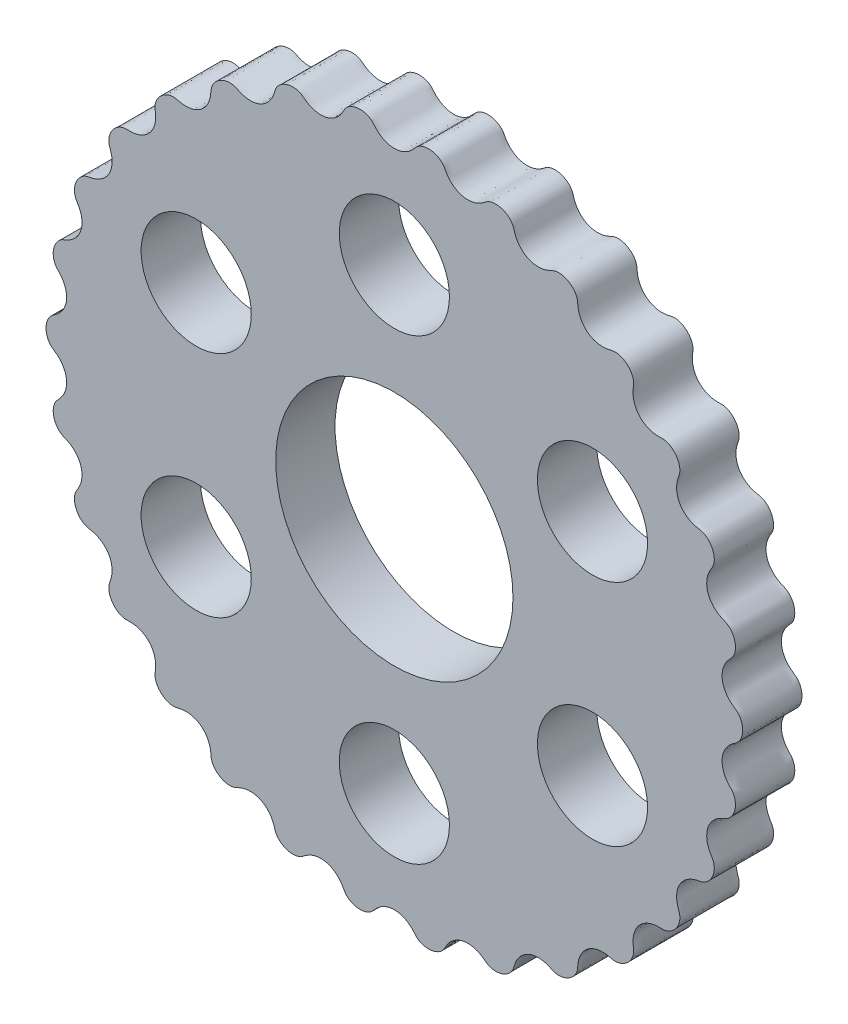
SolidWorks part; units mm, degrees
ref_plane "Front Plane" through (0, 0, 0) normal (0, 0, 1) x (1, 0, 0)
ref_plane "Top Plane" through (0, 0, 0) normal (0, 1, 0) x (1, 0, 0)
ref_plane "Right Plane" through (0, 0, 0) normal (1, 0, 0) x (0, 0, -1)
curve "Curve1"
sketch "Sketch1" plane through (0, 0, 0) normal (0, 0, 1) x (1, 0, 0)
  spline S0 degree 3 poles (1.507, 39.2179) (0, 38.6713) (-1.507, 39.2179) (-2.1962, 39.8832) (-2.4453, 40.1783) (-2.572, 40.3207) (-2.6813, 40.4255) (-2.8099, 40.5269) (-2.9733, 40.6297) (-3.1768, 40.7277) (-3.4191, 40.8108) (-3.6937, 40.869) (-3.9905, 40.8941) (-4.2968, 40.8813) (-4.5991, 40.8301) (-4.8841, 40.7439) (-5.1407, 40.6299) (-5.3604, 40.4982) (-5.5391, 40.36) (-5.6775, 40.2255) (-5.7822, 40.0996) (-5.8674, 39.9743) (-5.9616, 39.8087) (-6.144, 39.4683) (-6.6798, 38.6743) (-8.0402, 37.8262) (-9.6279, 38.0476) (-10.4403, 38.555) (-10.7454, 38.7919) (-10.8989, 38.9048) (-11.0277, 38.9846) (-11.1746, 39.0571) (-11.3557, 39.1237) (-11.5752, 39.1772) (-11.8294, 39.2082) (-12.1101, 39.2079) (-12.4056, 39.1708) (-12.7026, 39.0946) (-12.9876, 38.9817) (-13.2485, 38.8381) (-13.4758, 38.6732) (-13.6633, 38.4987) (-13.8094, 38.3265) (-13.9168, 38.1661) (-13.993, 38.0212) (-14.0503, 37.8809) (-14.108, 37.6993) (-14.2157, 37.3284) (-14.5746, 36.4403) (-15.729, 35.328) (-17.3281, 35.2144) (-18.2282, 35.5419) (-18.5759, 35.7101) (-18.7495, 35.7886) (-18.8921, 35.8399) (-19.0508, 35.8803) (-19.2418, 35.9077) (-19.4676, 35.9145) (-19.7228, 35.8919) (-19.9973, 35.8333) (-20.2786, 35.7355) (-20.5533, 35.5993) (-20.8086, 35.4295) (-21.0339, 35.2348) (-21.2219, 35.0264) (-21.3691, 34.8167) (-21.4761, 34.6178) (-21.5478, 34.4386) (-21.5923, 34.281) (-21.6191, 34.1319) (-21.6379, 33.9422) (-21.666, 33.5571) (-21.8325, 32.6138) (-22.7304, 31.2857) (-24.2709, 30.8422) (-25.2195, 30.9753) (-25.5945, 31.0676) (-25.7807, 31.1083) (-25.9308, 31.1289) (-26.0944, 31.1353) (-26.287, 31.1225) (-26.5092, 31.0821) (-26.7541, 31.007) (-27.0105, 30.8926) (-27.2653, 30.7385) (-27.5056, 30.5481) (-27.7201, 30.329) (-27.9, 30.0917) (-28.0406, 29.8487) (-28.1409, 29.613) (-28.2042, 29.3962) (-28.2371, 29.206) (-28.2478, 29.0426) (-28.2431, 28.8912) (-28.222, 28.7017) (-28.1695, 28.3191) (-28.1362, 27.3619) (-28.7384, 25.8761) (-30.153, 25.122) (-31.1085, 25.055) (-31.4945, 25.0673) (-31.6851, 25.0684) (-31.8362, 25.0573) (-31.9976, 25.0296) (-32.1833, 24.977) (-32.3923, 24.8913) (-32.6162, 24.7669) (-32.8432, 24.6017) (-33.0604, 24.398) (-33.2559, 24.1618) (-33.4201, 23.9029) (-33.5467, 23.6333) (-33.6337, 23.3664) (-33.6828, 23.115) (-33.6997, 22.8898) (-33.6924, 22.6969) (-33.6688, 22.5349) (-33.6327, 22.3877) (-33.5727, 22.2069) (-33.4418, 21.8435) (-33.2102, 20.9141) (-33.4903, 19.3356) (-34.7172, 18.3039) (-35.6379, 18.0397) (-36.0181, 17.9714) (-36.2047, 17.9329) (-36.3502, 17.8906) (-36.5023, 17.83) (-36.673, 17.7399) (-36.8596, 17.6127) (-37.0528, 17.4444) (-37.2405, 17.2357) (-37.4105, 16.9912) (-37.5527, 16.7195) (-37.6594, 16.4321) (-37.7273, 16.1421) (-37.7569, 15.863) (-37.7527, 15.6069) (-37.7224, 15.383) (-37.6751, 15.1959) (-37.6184, 15.0423) (-37.5524, 14.9059) (-37.4561, 14.7414) (-37.2525, 14.4133) (-36.8328, 13.5523) (-36.7786, 11.9501) (-37.7642, 10.6858) (-38.6098, 10.2359) (-38.9674, 10.0901) (-39.142, 10.0137) (-39.2755, 9.9421) (-39.4117, 9.8511) (-39.56, 9.7275) (-39.716, 9.5642) (-39.87, 9.3595) (-40.0101, 9.1163) (-40.1257, 8.8418) (-40.2082, 8.5465) (-40.2529, 8.2432) (-40.259, 7.9455) (-40.2299, 7.6663) (-40.1725, 7.4166) (-40.0963, 7.204) (-40.0112, 7.0308) (-39.9238, 6.8923) (-39.8309, 6.7726) (-39.7025, 6.6317) (-39.4351, 6.3531) (-38.8456, 5.5981) (-38.4595, 4.0423) (-39.1606, 2.6006) (-39.8943, 1.9848) (-40.2138, 1.7678) (-40.3686, 1.6568) (-40.4843, 1.559) (-40.5986, 1.4417) (-40.7179, 1.2899) (-40.8367, 1.0978) (-40.9447, 0.8655) (-41.0312, 0.5985) (-41.0872, 0.306) (-41.1065, 0) (-41.0872, -0.306) (-41.0312, -0.5985) (-40.9447, -0.8655) (-40.8367, -1.0978) (-40.7179, -1.2899) (-40.5986, -1.4417) (-40.4843, -1.559) (-40.3686, -1.6568) (-40.2138, -1.7678) (-39.8943, -1.9848) (-39.1606, -2.6006) (-38.4595, -4.0423) (-38.8456, -5.5981) (-39.4351, -6.3531) (-39.7025, -6.6317) (-39.8309, -6.7726) (-39.9238, -6.8923) (-40.0112, -7.0308) (-40.0963, -7.204) (-40.1725, -7.4166) (-40.2299, -7.6663) (-40.259, -7.9455) (-40.2529, -8.2432) (-40.2082, -8.5465) (-40.1257, -8.8418) (-40.0101, -9.1163) (-39.87, -9.3595) (-39.716, -9.5642) (-39.56, -9.7275) (-39.4117, -9.8511) (-39.2755, -9.9421) (-39.142, -10.0137) (-38.9674, -10.0901) (-38.6098, -10.2359) (-37.7642, -10.6858) (-36.7786, -11.9501) (-36.8328, -13.5523) (-37.2525, -14.4133) (-37.4561, -14.7414) (-37.5524, -14.9059) (-37.6184, -15.0423) (-37.6751, -15.1959) (-37.7224, -15.383) (-37.7527, -15.6069) (-37.7569, -15.863) (-37.7273, -16.1421) (-37.6594, -16.4321) (-37.5527, -16.7195) (-37.4105, -16.9912) (-37.2405, -17.2357) (-37.0528, -17.4444) (-36.8596, -17.6127) (-36.673, -17.7399) (-36.5023, -17.83) (-36.3502, -17.8906) (-36.2047, -17.9329) (-36.0181, -17.9714) (-35.6379, -18.0397) (-34.7172, -18.3039) (-33.4903, -19.3356) (-33.2102, -20.9141) (-33.4418, -21.8435) (-33.5727, -22.2069) (-33.6327, -22.3877) (-33.6688, -22.5349) (-33.6924, -22.6969) (-33.6997, -22.8898) (-33.6828, -23.115) (-33.6337, -23.3664) (-33.5467, -23.6333) (-33.4201, -23.9029) (-33.2559, -24.1618) (-33.0604, -24.398) (-32.8432, -24.6017) (-32.6162, -24.7669) (-32.3923, -24.8913) (-32.1833, -24.977) (-31.9976, -25.0296) (-31.8362, -25.0573) (-31.6851, -25.0684) (-31.4945, -25.0673) (-31.1085, -25.055) (-30.153, -25.122) (-28.7384, -25.8761) (-28.1362, -27.3619) (-28.1695, -28.3191) (-28.222, -28.7017) (-28.2431, -28.8912) (-28.2478, -29.0426) (-28.2371, -29.206) (-28.2042, -29.3962) (-28.1409, -29.613) (-28.0406, -29.8487) (-27.9, -30.0917) (-27.7201, -30.329) (-27.5056, -30.5481) (-27.2653, -30.7385) (-27.0105, -30.8926) (-26.7541, -31.007) (-26.5092, -31.0821) (-26.287, -31.1225) (-26.0944, -31.1353) (-25.9308, -31.1289) (-25.7807, -31.1083) (-25.5945, -31.0676) (-25.2195, -30.9753) (-24.2709, -30.8422) (-22.7304, -31.2857) (-21.8325, -32.6138) (-21.666, -33.5571) (-21.6379, -33.9422) (-21.6191, -34.1319) (-21.5923, -34.281) (-21.5478, -34.4386) (-21.4761, -34.6178) (-21.3691, -34.8167) (-21.2219, -35.0264) (-21.0339, -35.2348) (-20.8086, -35.4295) (-20.5533, -35.5993) (-20.2786, -35.7355) (-19.9973, -35.8333) (-19.7228, -35.8919) (-19.4676, -35.9145) (-19.2418, -35.9077) (-19.0508, -35.8803) (-18.8921, -35.8399) (-18.7495, -35.7886) (-18.5759, -35.7101) (-18.2282, -35.5419) (-17.3281, -35.2144) (-15.729, -35.328) (-14.5746, -36.4403) (-14.2157, -37.3284) (-14.108, -37.6993) (-14.0503, -37.8809) (-13.993, -38.0212) (-13.9168, -38.1661) (-13.8094, -38.3265) (-13.6633, -38.4987) (-13.4758, -38.6732) (-13.2485, -38.8381) (-12.9876, -38.9817) (-12.7026, -39.0946) (-12.4056, -39.1708) (-12.1101, -39.2079) (-11.8294, -39.2082) (-11.5752, -39.1772) (-11.3557, -39.1237) (-11.1746, -39.0571) (-11.0277, -38.9846) (-10.8989, -38.9048) (-10.7454, -38.7919) (-10.4403, -38.555) (-9.6279, -38.0476) (-8.0402, -37.8262) (-6.6798, -38.6743) (-6.144, -39.4683) (-5.9616, -39.8087) (-5.8674, -39.9743) (-5.7822, -40.0996) (-5.6775, -40.2255) (-5.5391, -40.36) (-5.3604, -40.4982) (-5.1407, -40.6299) (-4.8841, -40.7439) (-4.5991, -40.8301) (-4.2968, -40.8813) (-3.9905, -40.8941) (-3.6937, -40.869) (-3.4191, -40.8108) (-3.1768, -40.7277) (-2.9733, -40.6297) (-2.8099, -40.5269) (-2.6813, -40.4255) (-2.572, -40.3207) (-2.4453, -40.1783) (-2.1962, -39.8832) (-1.507, -39.2179) (0, -38.6713) (1.507, -39.2179) (2.1962, -39.8832) (2.4453, -40.1783) (2.572, -40.3207) (2.6813, -40.4255) (2.8099, -40.5269) (2.9733, -40.6297) (3.1768, -40.7277) (3.4191, -40.8108) (3.6937, -40.869) (3.9905, -40.8941) (4.2968, -40.8813) (4.5991, -40.8301) (4.8841, -40.7439) (5.1407, -40.6299) (5.3604, -40.4982) (5.5391, -40.36) (5.6775, -40.2255) (5.7822, -40.0996) (5.8674, -39.9743) (5.9616, -39.8087) (6.144, -39.4683) (6.6798, -38.6743) (8.0402, -37.8262) (9.6279, -38.0476) (10.4403, -38.555) (10.7454, -38.7919) (10.8989, -38.9048) (11.0277, -38.9846) (11.1746, -39.0571) (11.3557, -39.1237) (11.5752, -39.1772) (11.8294, -39.2082) (12.1101, -39.2079) (12.4056, -39.1708) (12.7026, -39.0946) (12.9876, -38.9817) (13.2485, -38.8381) (13.4758, -38.6732) (13.6633, -38.4987) (13.8094, -38.3265) (13.9168, -38.1661) (13.993, -38.0212) (14.0503, -37.8809) (14.108, -37.6993) (14.2157, -37.3284) (14.5746, -36.4403) (15.729, -35.328) (17.3281, -35.2144) (18.2282, -35.5419) (18.5759, -35.7101) (18.7495, -35.7886) (18.8921, -35.8399) (19.0508, -35.8803) (19.2418, -35.9077) (19.4676, -35.9145) (19.7228, -35.8919) (19.9973, -35.8333) (20.2786, -35.7355) (20.5533, -35.5993) (20.8086, -35.4295) (21.0339, -35.2348) (21.2219, -35.0264) (21.3691, -34.8167) (21.4761, -34.6178) (21.5478, -34.4386) (21.5923, -34.281) (21.6191, -34.1319) (21.6379, -33.9422) (21.666, -33.5571) (21.8325, -32.6138) (22.7304, -31.2857) (24.2709, -30.8422) (25.2195, -30.9753) (25.5945, -31.0676) (25.7807, -31.1083) (25.9308, -31.1289) (26.0944, -31.1353) (26.287, -31.1225) (26.5092, -31.0821) (26.7541, -31.007) (27.0105, -30.8926) (27.2653, -30.7385) (27.5056, -30.5481) (27.7201, -30.329) (27.9, -30.0917) (28.0406, -29.8487) (28.1409, -29.613) (28.2042, -29.3962) (28.2371, -29.206) (28.2478, -29.0426) (28.2431, -28.8912) (28.222, -28.7017) (28.1695, -28.3191) (28.1362, -27.3619) (28.7384, -25.8761) (30.153, -25.122) (31.1085, -25.055) (31.4945, -25.0673) (31.6851, -25.0684) (31.8362, -25.0573) (31.9976, -25.0296) (32.1833, -24.977) (32.3923, -24.8913) (32.6162, -24.7669) (32.8432, -24.6017) (33.0604, -24.398) (33.2559, -24.1618) (33.4201, -23.9029) (33.5467, -23.6333) (33.6337, -23.3664) (33.6828, -23.115) (33.6997, -22.8898) (33.6924, -22.6969) (33.6688, -22.5349) (33.6327, -22.3877) (33.5727, -22.2069) (33.4418, -21.8435) (33.2102, -20.9141) (33.4903, -19.3356) (34.7172, -18.3039) (35.6379, -18.0397) (36.0181, -17.9714) (36.2047, -17.9329) (36.3502, -17.8906) (36.5023, -17.83) (36.673, -17.7399) (36.8596, -17.6127) (37.0528, -17.4444) (37.2405, -17.2357) (37.4105, -16.9912) (37.5527, -16.7195) (37.6594, -16.4321) (37.7273, -16.1421) (37.7569, -15.863) (37.7527, -15.6069) (37.7224, -15.383) (37.6751, -15.1959) (37.6184, -15.0423) (37.5524, -14.9059) (37.4561, -14.7414) (37.2525, -14.4133) (36.8328, -13.5523) (36.7786, -11.9501) (37.7642, -10.6858) (38.6098, -10.2359) (38.9674, -10.0901) (39.142, -10.0137) (39.2755, -9.9421) (39.4117, -9.8511) (39.56, -9.7275) (39.716, -9.5642) (39.87, -9.3595) (40.0101, -9.1163) (40.1257, -8.8418) (40.2082, -8.5465) (40.2529, -8.2432) (40.259, -7.9455) (40.2299, -7.6663) (40.1725, -7.4166) (40.0963, -7.204) (40.0112, -7.0308) (39.9238, -6.8923) (39.8309, -6.7726) (39.7025, -6.6317) (39.4351, -6.3531) (38.8456, -5.5981) (38.4595, -4.0423) (39.1606, -2.6006) (39.8943, -1.9848) (40.2138, -1.7678) (40.3686, -1.6568) (40.4843, -1.559) (40.5986, -1.4417) (40.7179, -1.2899) (40.8367, -1.0978) (40.9447, -0.8655) (41.0312, -0.5985) (41.0872, -0.306) (41.1065, 0) (41.0872, 0.306) (41.0312, 0.5985) (40.9447, 0.8655) (40.8367, 1.0978) (40.7179, 1.2899) (40.5986, 1.4417) (40.4843, 1.559) (40.3686, 1.6568) (40.2138, 1.7678) (39.8943, 1.9848) (39.1606, 2.6006) (38.4595, 4.0423) (38.8456, 5.5981) (39.4351, 6.3531) (39.7025, 6.6317) (39.8309, 6.7726) (39.9238, 6.8923) (40.0112, 7.0308) (40.0963, 7.204) (40.1725, 7.4166) (40.2299, 7.6663) (40.259, 7.9455) (40.2529, 8.2432) (40.2082, 8.5465) (40.1257, 8.8418) (40.0101, 9.1163) (39.87, 9.3595) (39.716, 9.5642) (39.56, 9.7275) (39.4117, 9.8511) (39.2755, 9.9421) (39.142, 10.0137) (38.9674, 10.0901) (38.6098, 10.2359) (37.7642, 10.6858) (36.7786, 11.9501) (36.8328, 13.5523) (37.2525, 14.4133) (37.4561, 14.7414) (37.5524, 14.9059) (37.6184, 15.0423) (37.6751, 15.1959) (37.7224, 15.383) (37.7527, 15.6069) (37.7569, 15.863) (37.7273, 16.1421) (37.6594, 16.4321) (37.5527, 16.7195) (37.4105, 16.9912) (37.2405, 17.2357) (37.0528, 17.4444) (36.8596, 17.6127) (36.673, 17.7399) (36.5023, 17.83) (36.3502, 17.8906) (36.2047, 17.9329) (36.0181, 17.9714) (35.6379, 18.0397) (34.7172, 18.3039) (33.4903, 19.3356) (33.2102, 20.9141) (33.4418, 21.8435) (33.5727, 22.2069) (33.6327, 22.3877) (33.6688, 22.5349) (33.6924, 22.6969) (33.6997, 22.8898) (33.6828, 23.115) (33.6337, 23.3664) (33.5467, 23.6333) (33.4201, 23.9029) (33.2559, 24.1618) (33.0604, 24.398) (32.8432, 24.6017) (32.6162, 24.7669) (32.3923, 24.8913) (32.1833, 24.977) (31.9976, 25.0296) (31.8362, 25.0573) (31.6851, 25.0684) (31.4945, 25.0673) (31.1085, 25.055) (30.153, 25.122) (28.7384, 25.8761) (28.1362, 27.3619) (28.1695, 28.3191) (28.222, 28.7017) (28.2431, 28.8912) (28.2478, 29.0426) (28.2371, 29.206) (28.2042, 29.3962) (28.1409, 29.613) (28.0406, 29.8487) (27.9, 30.0917) (27.7201, 30.329) (27.5056, 30.5481) (27.2653, 30.7385) (27.0105, 30.8926) (26.7541, 31.007) (26.5092, 31.0821) (26.287, 31.1225) (26.0944, 31.1353) (25.9308, 31.1289) (25.7807, 31.1083) (25.5945, 31.0676) (25.2195, 30.9753) (24.2709, 30.8422) (22.7304, 31.2857) (21.8325, 32.6138) (21.666, 33.5571) (21.6379, 33.9422) (21.6191, 34.1319) (21.5923, 34.281) (21.5478, 34.4386) (21.4761, 34.6178) (21.3691, 34.8167) (21.2219, 35.0264) (21.0339, 35.2348) (20.8086, 35.4295) (20.5533, 35.5993) (20.2786, 35.7355) (19.9973, 35.8333) (19.7228, 35.8919) (19.4676, 35.9145) (19.2418, 35.9077) (19.0508, 35.8803) (18.8921, 35.8399) (18.7495, 35.7886) (18.5759, 35.7101) (18.2282, 35.5419) (17.3281, 35.2144) (15.729, 35.328) (14.5746, 36.4403) (14.2157, 37.3284) (14.108, 37.6993) (14.0503, 37.8809) (13.993, 38.0212) (13.9168, 38.1661) (13.8094, 38.3265) (13.6633, 38.4987) (13.4758, 38.6732) (13.2485, 38.8381) (12.9876, 38.9817) (12.7026, 39.0946) (12.4056, 39.1708) (12.1101, 39.2079) (11.8294, 39.2082) (11.5752, 39.1772) (11.3557, 39.1237) (11.1746, 39.0571) (11.0277, 38.9846) (10.8989, 38.9048) (10.7454, 38.7919) (10.4403, 38.555) (9.6279, 38.0476) (8.0402, 37.8262) (6.6798, 38.6743) (6.144, 39.4683) (5.9616, 39.8087) (5.8674, 39.9743) (5.7822, 40.0996) (5.6775, 40.2255) (5.5391, 40.36) (5.3604, 40.4982) (5.1407, 40.6299) (4.8841, 40.7439) (4.5991, 40.8301) (4.2968, 40.8813) (3.9905, 40.8941) (3.6937, 40.869) (3.4191, 40.8108) (3.1768, 40.7277) (2.9733, 40.6297) (2.8099, 40.5269) (2.6813, 40.4255) (2.572, 40.3207) (2.4453, 40.1783) (2.1962, 39.8832) (1.507, 39.2179) (0, 38.6713) (-1.507, 39.2179) knots -0.009771 -0.008826 -0.006349 0 0.006349 0.008826 0.009771 0.010301 0.010776 0.01132 0.011975 0.012747 0.013626 0.01459 0.015613 0.016667 0.01772 0.018743 0.019707 0.020586 0.021359 0.022014 0.022558 0.023032 0.023562 0.024507 0.026985 0.033333 0.039682 0.042159 0.043104 0.043635 0.044109 0.044653 0.045308 0.046081 0.04696 0.047924 0.048947 0.05 0.051053 0.052076 0.05304 0.053919 0.054692 0.055347 0.055891 0.056365 0.056896 0.057841 0.060318 0.066667 0.073015 0.075493 0.076438 0.076968 0.077442 0.077986 0.078641 0.079414 0.080293 0.081257 0.08228 0.083333 0.084387 0.08541 0.086374 0.087253 0.088025 0.08868 0.089224 0.089699 0.090229 0.091174 0.093651 0.1 0.106349 0.108826 0.109771 0.110301 0.110776 0.11132 0.111975 0.112747 0.113626 0.11459 0.115613 0.116667 0.11772 0.118743 0.119707 0.120586 0.121359 0.122014 0.122558 0.123032 0.123562 0.124507 0.126985 0.133333 0.139682 0.142159 0.143104 0.143635 0.144109 0.144653 0.145308 0.146081 0.14696 0.147924 0.148947 0.15 0.151053 0.152076 0.15304 0.153919 0.154692 0.155347 0.155891 0.156365 0.156896 0.157841 0.160318 0.166667 0.173015 0.175493 0.176437 0.176968 0.177442 0.177986 0.178641 0.179414 0.180293 0.181257 0.18228 0.183333 0.184387 0.18541 0.186374 0.187253 0.188025 0.18868 0.189224 0.189699 0.190229 0.191174 0.193651 0.2 0.206349 0.208826 0.209771 0.210301 0.210776 0.21132 0.211975 0.212747 0.213626 0.21459 0.215613 0.216667 0.21772 0.218743 0.219707 0.220586 0.221359 0.222014 0.222558 0.223032 0.223563 0.224507 0.226985 0.233333 0.239682 0.242159 0.243104 0.243635 0.244109 0.244653 0.245308 0.246081 0.24696 0.247924 0.248947 0.25 0.251053 0.252076 0.25304 0.253919 0.254692 0.255347 0.255891 0.256365 0.256896 0.257841 0.260318 0.266667 0.273015 0.275493 0.276437 0.276968 0.277442 0.277986 0.278641 0.279414 0.280293 0.281257 0.28228 0.283333 0.284387 0.28541 0.286374 0.287253 0.288025 0.28868 0.289224 0.289699 0.290229 0.291174 0.293651 0.3 0.306349 0.308826 0.309771 0.310301 0.310776 0.31132 0.311975 0.312747 0.313626 0.31459 0.315613 0.316667 0.31772 0.318743 0.319707 0.320586 0.321359 0.322014 0.322558 0.323032 0.323563 0.324507 0.326985 0.333333 0.339682 0.342159 0.343104 0.343635 0.344109 0.344653 0.345308 0.346081 0.34696 0.347924 0.348947 0.35 0.351053 0.352076 0.35304 0.353919 0.354692 0.355347 0.355891 0.356365 0.356896 0.357841 0.360318 0.366667 0.373015 0.375493 0.376438 0.376968 0.377442 0.377986 0.378641 0.379414 0.380293 0.381257 0.38228 0.383333 0.384387 0.38541 0.386374 0.387253 0.388025 0.38868 0.389224 0.389699 0.390229 0.391174 0.393651 0.4 0.406349 0.408826 0.409771 0.410301 0.410776 0.41132 0.411975 0.412747 0.413626 0.41459 0.415613 0.416667 0.41772 0.418743 0.419707 0.420586 0.421359 0.422014 0.422558 0.423032 0.423562 0.424507 0.426985 0.433333 0.439682 0.442159 0.443104 0.443635 0.444109 0.444653 0.445308 0.446081 0.44696 0.447924 0.448947 0.45 0.451053 0.452076 0.45304 0.453919 0.454692 0.455347 0.455891 0.456365 0.456896 0.457841 0.460318 0.466667 0.473015 0.475493 0.476438 0.476968 0.477442 0.477986 0.478641 0.479414 0.480293 0.481257 0.48228 0.483333 0.484387 0.48541 0.486374 0.487253 0.488025 0.48868 0.489224 0.489699 0.490229 0.491174 0.493651 0.5 0.506349 0.508826 0.509771 0.510301 0.510776 0.51132 0.511975 0.512747 0.513626 0.51459 0.515613 0.516667 0.51772 0.518743 0.519707 0.520586 0.521359 0.522014 0.522558 0.523032 0.523562 0.524507 0.526985 0.533333 0.539682 0.542159 0.543104 0.543635 0.544109 0.544653 0.545308 0.546081 0.54696 0.547924 0.548947 0.55 0.551053 0.552076 0.55304 0.553919 0.554692 0.555347 0.555891 0.556365 0.556896 0.557841 0.560318 0.566667 0.573015 0.575493 0.576438 0.576968 0.577442 0.577986 0.578641 0.579414 0.580293 0.581257 0.58228 0.583333 0.584387 0.58541 0.586374 0.587253 0.588025 0.58868 0.589224 0.589699 0.590229 0.591174 0.593651 0.6 0.606349 0.608826 0.609771 0.610301 0.610776 0.61132 0.611975 0.612747 0.613626 0.61459 0.615613 0.616667 0.61772 0.618743 0.619707 0.620586 0.621359 0.622014 0.622558 0.623032 0.623562 0.624507 0.626985 0.633333 0.639682 0.642159 0.643104 0.643635 0.644109 0.644653 0.645308 0.646081 0.64696 0.647924 0.648947 0.65 0.651053 0.652076 0.65304 0.653919 0.654692 0.655347 0.655891 0.656365 0.656896 0.657841 0.660318 0.666667 0.673015 0.675493 0.676437 0.676968 0.677442 0.677986 0.678641 0.679414 0.680293 0.681257 0.68228 0.683333 0.684387 0.68541 0.686374 0.687253 0.688025 0.68868 0.689224 0.689699 0.690229 0.691174 0.693651 0.7 0.706349 0.708826 0.709771 0.710301 0.710776 0.71132 0.711975 0.712747 0.713626 0.71459 0.715613 0.716667 0.71772 0.718743 0.719707 0.720586 0.721359 0.722014 0.722558 0.723032 0.723563 0.724507 0.726985 0.733333 0.739682 0.742159 0.743104 0.743635 0.744109 0.744653 0.745308 0.746081 0.74696 0.747924 0.748947 0.75 0.751053 0.752076 0.75304 0.753919 0.754692 0.755347 0.755891 0.756365 0.756896 0.757841 0.760318 0.766667 0.773015 0.775493 0.776437 0.776968 0.777442 0.777986 0.778641 0.779414 0.780293 0.781257 0.78228 0.783333 0.784387 0.78541 0.786374 0.787253 0.788025 0.78868 0.789224 0.789699 0.790229 0.791174 0.793651 0.8 0.806349 0.808826 0.809771 0.810301 0.810776 0.81132 0.811975 0.812747 0.813626 0.81459 0.815613 0.816667 0.81772 0.818743 0.819707 0.820586 0.821359 0.822014 0.822558 0.823032 0.823563 0.824507 0.826985 0.833333 0.839682 0.842159 0.843104 0.843635 0.844109 0.844653 0.845308 0.846081 0.84696 0.847924 0.848947 0.85 0.851053 0.852076 0.85304 0.853919 0.854692 0.855347 0.855891 0.856365 0.856896 0.857841 0.860318 0.866667 0.873015 0.875493 0.876438 0.876968 0.877442 0.877986 0.878641 0.879414 0.880293 0.881257 0.88228 0.883333 0.884387 0.88541 0.886374 0.887253 0.888025 0.88868 0.889224 0.889699 0.890229 0.891174 0.893651 0.9 0.906349 0.908826 0.909771 0.910301 0.910776 0.91132 0.911975 0.912747 0.913626 0.91459 0.915613 0.916667 0.91772 0.918743 0.919707 0.920586 0.921359 0.922014 0.922558 0.923032 0.923562 0.924507 0.926985 0.933333 0.939682 0.942159 0.943104 0.943635 0.944109 0.944653 0.945308 0.946081 0.94696 0.947924 0.948947 0.95 0.951053 0.952076 0.95304 0.953919 0.954692 0.955347 0.955891 0.956365 0.956896 0.957841 0.960318 0.966667 0.973015 0.975493 0.976438 0.976968 0.977442 0.977986 0.978641 0.979414 0.980293 0.981257 0.98228 0.983333 0.984387 0.98541 0.986374 0.987253 0.988025 0.98868 0.989224 0.989699 0.990229 0.991174 0.993651 1 1.006349 1.008826 1.009771 only from (0, 38.9) to (0, 38.9) construction
  spline S1 degree 3 poles (1.507, 39.2179) (0, 38.6713) (-1.507, 39.2179) (-2.1962, 39.8832) (-2.4453, 40.1783) (-2.572, 40.3207) (-2.6813, 40.4255) (-2.8099, 40.5269) (-2.9733, 40.6297) (-3.1768, 40.7277) (-3.4191, 40.8108) (-3.6937, 40.869) (-3.9905, 40.8941) (-4.2968, 40.8813) (-4.5991, 40.8301) (-4.8841, 40.7439) (-5.1407, 40.6299) (-5.3604, 40.4982) (-5.5391, 40.36) (-5.6775, 40.2255) (-5.7822, 40.0996) (-5.8674, 39.9743) (-5.9616, 39.8087) (-6.144, 39.4683) (-6.6798, 38.6743) (-8.0402, 37.8262) (-9.6279, 38.0476) (-10.4403, 38.555) (-10.7454, 38.7919) (-10.8989, 38.9048) (-11.0277, 38.9846) (-11.1746, 39.0571) (-11.3557, 39.1237) (-11.5752, 39.1772) (-11.8294, 39.2082) (-12.1101, 39.2079) (-12.4056, 39.1708) (-12.7026, 39.0946) (-12.9876, 38.9817) (-13.2485, 38.8381) (-13.4758, 38.6732) (-13.6633, 38.4987) (-13.8094, 38.3265) (-13.9168, 38.1661) (-13.993, 38.0212) (-14.0503, 37.8809) (-14.108, 37.6993) (-14.2157, 37.3284) (-14.5746, 36.4403) (-15.729, 35.328) (-17.3281, 35.2144) (-18.2282, 35.5419) (-18.5759, 35.7101) (-18.7495, 35.7886) (-18.8921, 35.8399) (-19.0508, 35.8803) (-19.2418, 35.9077) (-19.4676, 35.9145) (-19.7228, 35.8919) (-19.9973, 35.8333) (-20.2786, 35.7355) (-20.5533, 35.5993) (-20.8086, 35.4295) (-21.0339, 35.2348) (-21.2219, 35.0264) (-21.3691, 34.8167) (-21.4761, 34.6178) (-21.5478, 34.4386) (-21.5923, 34.281) (-21.6191, 34.1319) (-21.6379, 33.9422) (-21.666, 33.5571) (-21.8325, 32.6138) (-22.7304, 31.2857) (-24.2709, 30.8422) (-25.2195, 30.9753) (-25.5945, 31.0676) (-25.7807, 31.1083) (-25.9308, 31.1289) (-26.0944, 31.1353) (-26.287, 31.1225) (-26.5092, 31.0821) (-26.7541, 31.007) (-27.0105, 30.8926) (-27.2653, 30.7385) (-27.5056, 30.5481) (-27.7201, 30.329) (-27.9, 30.0917) (-28.0406, 29.8487) (-28.1409, 29.613) (-28.2042, 29.3962) (-28.2371, 29.206) (-28.2478, 29.0426) (-28.2431, 28.8912) (-28.222, 28.7017) (-28.1695, 28.3191) (-28.1362, 27.3619) (-28.7384, 25.8761) (-30.153, 25.122) (-31.1085, 25.055) (-31.4945, 25.0673) (-31.6851, 25.0684) (-31.8362, 25.0573) (-31.9976, 25.0296) (-32.1833, 24.977) (-32.3923, 24.8913) (-32.6162, 24.7669) (-32.8432, 24.6017) (-33.0604, 24.398) (-33.2559, 24.1618) (-33.4201, 23.9029) (-33.5467, 23.6333) (-33.6337, 23.3664) (-33.6828, 23.115) (-33.6997, 22.8898) (-33.6924, 22.6969) (-33.6688, 22.5349) (-33.6327, 22.3877) (-33.5727, 22.2069) (-33.4418, 21.8435) (-33.2102, 20.9141) (-33.4903, 19.3356) (-34.7172, 18.3039) (-35.6379, 18.0397) (-36.0181, 17.9714) (-36.2047, 17.9329) (-36.3502, 17.8906) (-36.5023, 17.83) (-36.673, 17.7399) (-36.8596, 17.6127) (-37.0528, 17.4444) (-37.2405, 17.2357) (-37.4105, 16.9912) (-37.5527, 16.7195) (-37.6594, 16.4321) (-37.7273, 16.1421) (-37.7569, 15.863) (-37.7527, 15.6069) (-37.7224, 15.383) (-37.6751, 15.1959) (-37.6184, 15.0423) (-37.5524, 14.9059) (-37.4561, 14.7414) (-37.2525, 14.4133) (-36.8328, 13.5523) (-36.7786, 11.9501) (-37.7642, 10.6858) (-38.6098, 10.2359) (-38.9674, 10.0901) (-39.142, 10.0137) (-39.2755, 9.9421) (-39.4117, 9.8511) (-39.56, 9.7275) (-39.716, 9.5642) (-39.87, 9.3595) (-40.0101, 9.1163) (-40.1257, 8.8418) (-40.2082, 8.5465) (-40.2529, 8.2432) (-40.259, 7.9455) (-40.2299, 7.6663) (-40.1725, 7.4166) (-40.0963, 7.204) (-40.0112, 7.0308) (-39.9238, 6.8923) (-39.8309, 6.7726) (-39.7025, 6.6317) (-39.4351, 6.3531) (-38.8456, 5.5981) (-38.4595, 4.0423) (-39.1606, 2.6006) (-39.8943, 1.9848) (-40.2138, 1.7678) (-40.3686, 1.6568) (-40.4843, 1.559) (-40.5986, 1.4417) (-40.7179, 1.2899) (-40.8367, 1.0978) (-40.9447, 0.8655) (-41.0312, 0.5985) (-41.0872, 0.306) (-41.1065, 0) (-41.0872, -0.306) (-41.0312, -0.5985) (-40.9447, -0.8655) (-40.8367, -1.0978) (-40.7179, -1.2899) (-40.5986, -1.4417) (-40.4843, -1.559) (-40.3686, -1.6568) (-40.2138, -1.7678) (-39.8943, -1.9848) (-39.1606, -2.6006) (-38.4595, -4.0423) (-38.8456, -5.5981) (-39.4351, -6.3531) (-39.7025, -6.6317) (-39.8309, -6.7726) (-39.9238, -6.8923) (-40.0112, -7.0308) (-40.0963, -7.204) (-40.1725, -7.4166) (-40.2299, -7.6663) (-40.259, -7.9455) (-40.2529, -8.2432) (-40.2082, -8.5465) (-40.1257, -8.8418) (-40.0101, -9.1163) (-39.87, -9.3595) (-39.716, -9.5642) (-39.56, -9.7275) (-39.4117, -9.8511) (-39.2755, -9.9421) (-39.142, -10.0137) (-38.9674, -10.0901) (-38.6098, -10.2359) (-37.7642, -10.6858) (-36.7786, -11.9501) (-36.8328, -13.5523) (-37.2525, -14.4133) (-37.4561, -14.7414) (-37.5524, -14.9059) (-37.6184, -15.0423) (-37.6751, -15.1959) (-37.7224, -15.383) (-37.7527, -15.6069) (-37.7569, -15.863) (-37.7273, -16.1421) (-37.6594, -16.4321) (-37.5527, -16.7195) (-37.4105, -16.9912) (-37.2405, -17.2357) (-37.0528, -17.4444) (-36.8596, -17.6127) (-36.673, -17.7399) (-36.5023, -17.83) (-36.3502, -17.8906) (-36.2047, -17.9329) (-36.0181, -17.9714) (-35.6379, -18.0397) (-34.7172, -18.3039) (-33.4903, -19.3356) (-33.2102, -20.9141) (-33.4418, -21.8435) (-33.5727, -22.2069) (-33.6327, -22.3877) (-33.6688, -22.5349) (-33.6924, -22.6969) (-33.6997, -22.8898) (-33.6828, -23.115) (-33.6337, -23.3664) (-33.5467, -23.6333) (-33.4201, -23.9029) (-33.2559, -24.1618) (-33.0604, -24.398) (-32.8432, -24.6017) (-32.6162, -24.7669) (-32.3923, -24.8913) (-32.1833, -24.977) (-31.9976, -25.0296) (-31.8362, -25.0573) (-31.6851, -25.0684) (-31.4945, -25.0673) (-31.1085, -25.055) (-30.153, -25.122) (-28.7384, -25.8761) (-28.1362, -27.3619) (-28.1695, -28.3191) (-28.222, -28.7017) (-28.2431, -28.8912) (-28.2478, -29.0426) (-28.2371, -29.206) (-28.2042, -29.3962) (-28.1409, -29.613) (-28.0406, -29.8487) (-27.9, -30.0917) (-27.7201, -30.329) (-27.5056, -30.5481) (-27.2653, -30.7385) (-27.0105, -30.8926) (-26.7541, -31.007) (-26.5092, -31.0821) (-26.287, -31.1225) (-26.0944, -31.1353) (-25.9308, -31.1289) (-25.7807, -31.1083) (-25.5945, -31.0676) (-25.2195, -30.9753) (-24.2709, -30.8422) (-22.7304, -31.2857) (-21.8325, -32.6138) (-21.666, -33.5571) (-21.6379, -33.9422) (-21.6191, -34.1319) (-21.5923, -34.281) (-21.5478, -34.4386) (-21.4761, -34.6178) (-21.3691, -34.8167) (-21.2219, -35.0264) (-21.0339, -35.2348) (-20.8086, -35.4295) (-20.5533, -35.5993) (-20.2786, -35.7355) (-19.9973, -35.8333) (-19.7228, -35.8919) (-19.4676, -35.9145) (-19.2418, -35.9077) (-19.0508, -35.8803) (-18.8921, -35.8399) (-18.7495, -35.7886) (-18.5759, -35.7101) (-18.2282, -35.5419) (-17.3281, -35.2144) (-15.729, -35.328) (-14.5746, -36.4403) (-14.2157, -37.3284) (-14.108, -37.6993) (-14.0503, -37.8809) (-13.993, -38.0212) (-13.9168, -38.1661) (-13.8094, -38.3265) (-13.6633, -38.4987) (-13.4758, -38.6732) (-13.2485, -38.8381) (-12.9876, -38.9817) (-12.7026, -39.0946) (-12.4056, -39.1708) (-12.1101, -39.2079) (-11.8294, -39.2082) (-11.5752, -39.1772) (-11.3557, -39.1237) (-11.1746, -39.0571) (-11.0277, -38.9846) (-10.8989, -38.9048) (-10.7454, -38.7919) (-10.4403, -38.555) (-9.6279, -38.0476) (-8.0402, -37.8262) (-6.6798, -38.6743) (-6.144, -39.4683) (-5.9616, -39.8087) (-5.8674, -39.9743) (-5.7822, -40.0996) (-5.6775, -40.2255) (-5.5391, -40.36) (-5.3604, -40.4982) (-5.1407, -40.6299) (-4.8841, -40.7439) (-4.5991, -40.8301) (-4.2968, -40.8813) (-3.9905, -40.8941) (-3.6937, -40.869) (-3.4191, -40.8108) (-3.1768, -40.7277) (-2.9733, -40.6297) (-2.8099, -40.5269) (-2.6813, -40.4255) (-2.572, -40.3207) (-2.4453, -40.1783) (-2.1962, -39.8832) (-1.507, -39.2179) (0, -38.6713) (1.507, -39.2179) (2.1962, -39.8832) (2.4453, -40.1783) (2.572, -40.3207) (2.6813, -40.4255) (2.8099, -40.5269) (2.9733, -40.6297) (3.1768, -40.7277) (3.4191, -40.8108) (3.6937, -40.869) (3.9905, -40.8941) (4.2968, -40.8813) (4.5991, -40.8301) (4.8841, -40.7439) (5.1407, -40.6299) (5.3604, -40.4982) (5.5391, -40.36) (5.6775, -40.2255) (5.7822, -40.0996) (5.8674, -39.9743) (5.9616, -39.8087) (6.144, -39.4683) (6.6798, -38.6743) (8.0402, -37.8262) (9.6279, -38.0476) (10.4403, -38.555) (10.7454, -38.7919) (10.8989, -38.9048) (11.0277, -38.9846) (11.1746, -39.0571) (11.3557, -39.1237) (11.5752, -39.1772) (11.8294, -39.2082) (12.1101, -39.2079) (12.4056, -39.1708) (12.7026, -39.0946) (12.9876, -38.9817) (13.2485, -38.8381) (13.4758, -38.6732) (13.6633, -38.4987) (13.8094, -38.3265) (13.9168, -38.1661) (13.993, -38.0212) (14.0503, -37.8809) (14.108, -37.6993) (14.2157, -37.3284) (14.5746, -36.4403) (15.729, -35.328) (17.3281, -35.2144) (18.2282, -35.5419) (18.5759, -35.7101) (18.7495, -35.7886) (18.8921, -35.8399) (19.0508, -35.8803) (19.2418, -35.9077) (19.4676, -35.9145) (19.7228, -35.8919) (19.9973, -35.8333) (20.2786, -35.7355) (20.5533, -35.5993) (20.8086, -35.4295) (21.0339, -35.2348) (21.2219, -35.0264) (21.3691, -34.8167) (21.4761, -34.6178) (21.5478, -34.4386) (21.5923, -34.281) (21.6191, -34.1319) (21.6379, -33.9422) (21.666, -33.5571) (21.8325, -32.6138) (22.7304, -31.2857) (24.2709, -30.8422) (25.2195, -30.9753) (25.5945, -31.0676) (25.7807, -31.1083) (25.9308, -31.1289) (26.0944, -31.1353) (26.287, -31.1225) (26.5092, -31.0821) (26.7541, -31.007) (27.0105, -30.8926) (27.2653, -30.7385) (27.5056, -30.5481) (27.7201, -30.329) (27.9, -30.0917) (28.0406, -29.8487) (28.1409, -29.613) (28.2042, -29.3962) (28.2371, -29.206) (28.2478, -29.0426) (28.2431, -28.8912) (28.222, -28.7017) (28.1695, -28.3191) (28.1362, -27.3619) (28.7384, -25.8761) (30.153, -25.122) (31.1085, -25.055) (31.4945, -25.0673) (31.6851, -25.0684) (31.8362, -25.0573) (31.9976, -25.0296) (32.1833, -24.977) (32.3923, -24.8913) (32.6162, -24.7669) (32.8432, -24.6017) (33.0604, -24.398) (33.2559, -24.1618) (33.4201, -23.9029) (33.5467, -23.6333) (33.6337, -23.3664) (33.6828, -23.115) (33.6997, -22.8898) (33.6924, -22.6969) (33.6688, -22.5349) (33.6327, -22.3877) (33.5727, -22.2069) (33.4418, -21.8435) (33.2102, -20.9141) (33.4903, -19.3356) (34.7172, -18.3039) (35.6379, -18.0397) (36.0181, -17.9714) (36.2047, -17.9329) (36.3502, -17.8906) (36.5023, -17.83) (36.673, -17.7399) (36.8596, -17.6127) (37.0528, -17.4444) (37.2405, -17.2357) (37.4105, -16.9912) (37.5527, -16.7195) (37.6594, -16.4321) (37.7273, -16.1421) (37.7569, -15.863) (37.7527, -15.6069) (37.7224, -15.383) (37.6751, -15.1959) (37.6184, -15.0423) (37.5524, -14.9059) (37.4561, -14.7414) (37.2525, -14.4133) (36.8328, -13.5523) (36.7786, -11.9501) (37.7642, -10.6858) (38.6098, -10.2359) (38.9674, -10.0901) (39.142, -10.0137) (39.2755, -9.9421) (39.4117, -9.8511) (39.56, -9.7275) (39.716, -9.5642) (39.87, -9.3595) (40.0101, -9.1163) (40.1257, -8.8418) (40.2082, -8.5465) (40.2529, -8.2432) (40.259, -7.9455) (40.2299, -7.6663) (40.1725, -7.4166) (40.0963, -7.204) (40.0112, -7.0308) (39.9238, -6.8923) (39.8309, -6.7726) (39.7025, -6.6317) (39.4351, -6.3531) (38.8456, -5.5981) (38.4595, -4.0423) (39.1606, -2.6006) (39.8943, -1.9848) (40.2138, -1.7678) (40.3686, -1.6568) (40.4843, -1.559) (40.5986, -1.4417) (40.7179, -1.2899) (40.8367, -1.0978) (40.9447, -0.8655) (41.0312, -0.5985) (41.0872, -0.306) (41.1065, 0) (41.0872, 0.306) (41.0312, 0.5985) (40.9447, 0.8655) (40.8367, 1.0978) (40.7179, 1.2899) (40.5986, 1.4417) (40.4843, 1.559) (40.3686, 1.6568) (40.2138, 1.7678) (39.8943, 1.9848) (39.1606, 2.6006) (38.4595, 4.0423) (38.8456, 5.5981) (39.4351, 6.3531) (39.7025, 6.6317) (39.8309, 6.7726) (39.9238, 6.8923) (40.0112, 7.0308) (40.0963, 7.204) (40.1725, 7.4166) (40.2299, 7.6663) (40.259, 7.9455) (40.2529, 8.2432) (40.2082, 8.5465) (40.1257, 8.8418) (40.0101, 9.1163) (39.87, 9.3595) (39.716, 9.5642) (39.56, 9.7275) (39.4117, 9.8511) (39.2755, 9.9421) (39.142, 10.0137) (38.9674, 10.0901) (38.6098, 10.2359) (37.7642, 10.6858) (36.7786, 11.9501) (36.8328, 13.5523) (37.2525, 14.4133) (37.4561, 14.7414) (37.5524, 14.9059) (37.6184, 15.0423) (37.6751, 15.1959) (37.7224, 15.383) (37.7527, 15.6069) (37.7569, 15.863) (37.7273, 16.1421) (37.6594, 16.4321) (37.5527, 16.7195) (37.4105, 16.9912) (37.2405, 17.2357) (37.0528, 17.4444) (36.8596, 17.6127) (36.673, 17.7399) (36.5023, 17.83) (36.3502, 17.8906) (36.2047, 17.9329) (36.0181, 17.9714) (35.6379, 18.0397) (34.7172, 18.3039) (33.4903, 19.3356) (33.2102, 20.9141) (33.4418, 21.8435) (33.5727, 22.2069) (33.6327, 22.3877) (33.6688, 22.5349) (33.6924, 22.6969) (33.6997, 22.8898) (33.6828, 23.115) (33.6337, 23.3664) (33.5467, 23.6333) (33.4201, 23.9029) (33.2559, 24.1618) (33.0604, 24.398) (32.8432, 24.6017) (32.6162, 24.7669) (32.3923, 24.8913) (32.1833, 24.977) (31.9976, 25.0296) (31.8362, 25.0573) (31.6851, 25.0684) (31.4945, 25.0673) (31.1085, 25.055) (30.153, 25.122) (28.7384, 25.8761) (28.1362, 27.3619) (28.1695, 28.3191) (28.222, 28.7017) (28.2431, 28.8912) (28.2478, 29.0426) (28.2371, 29.206) (28.2042, 29.3962) (28.1409, 29.613) (28.0406, 29.8487) (27.9, 30.0917) (27.7201, 30.329) (27.5056, 30.5481) (27.2653, 30.7385) (27.0105, 30.8926) (26.7541, 31.007) (26.5092, 31.0821) (26.287, 31.1225) (26.0944, 31.1353) (25.9308, 31.1289) (25.7807, 31.1083) (25.5945, 31.0676) (25.2195, 30.9753) (24.2709, 30.8422) (22.7304, 31.2857) (21.8325, 32.6138) (21.666, 33.5571) (21.6379, 33.9422) (21.6191, 34.1319) (21.5923, 34.281) (21.5478, 34.4386) (21.4761, 34.6178) (21.3691, 34.8167) (21.2219, 35.0264) (21.0339, 35.2348) (20.8086, 35.4295) (20.5533, 35.5993) (20.2786, 35.7355) (19.9973, 35.8333) (19.7228, 35.8919) (19.4676, 35.9145) (19.2418, 35.9077) (19.0508, 35.8803) (18.8921, 35.8399) (18.7495, 35.7886) (18.5759, 35.7101) (18.2282, 35.5419) (17.3281, 35.2144) (15.729, 35.328) (14.5746, 36.4403) (14.2157, 37.3284) (14.108, 37.6993) (14.0503, 37.8809) (13.993, 38.0212) (13.9168, 38.1661) (13.8094, 38.3265) (13.6633, 38.4987) (13.4758, 38.6732) (13.2485, 38.8381) (12.9876, 38.9817) (12.7026, 39.0946) (12.4056, 39.1708) (12.1101, 39.2079) (11.8294, 39.2082) (11.5752, 39.1772) (11.3557, 39.1237) (11.1746, 39.0571) (11.0277, 38.9846) (10.8989, 38.9048) (10.7454, 38.7919) (10.4403, 38.555) (9.6279, 38.0476) (8.0402, 37.8262) (6.6798, 38.6743) (6.144, 39.4683) (5.9616, 39.8087) (5.8674, 39.9743) (5.7822, 40.0996) (5.6775, 40.2255) (5.5391, 40.36) (5.3604, 40.4982) (5.1407, 40.6299) (4.8841, 40.7439) (4.5991, 40.8301) (4.2968, 40.8813) (3.9905, 40.8941) (3.6937, 40.869) (3.4191, 40.8108) (3.1768, 40.7277) (2.9733, 40.6297) (2.8099, 40.5269) (2.6813, 40.4255) (2.572, 40.3207) (2.4453, 40.1783) (2.1962, 39.8832) (1.507, 39.2179) (0, 38.6713) (-1.507, 39.2179) knots -0.009771 -0.008826 -0.006349 0 0.006349 0.008826 0.009771 0.010301 0.010776 0.01132 0.011975 0.012747 0.013626 0.01459 0.015613 0.016667 0.01772 0.018743 0.019707 0.020586 0.021359 0.022014 0.022558 0.023032 0.023562 0.024507 0.026985 0.033333 0.039682 0.042159 0.043104 0.043635 0.044109 0.044653 0.045308 0.046081 0.04696 0.047924 0.048947 0.05 0.051053 0.052076 0.05304 0.053919 0.054692 0.055347 0.055891 0.056365 0.056896 0.057841 0.060318 0.066667 0.073015 0.075493 0.076438 0.076968 0.077442 0.077986 0.078641 0.079414 0.080293 0.081257 0.08228 0.083333 0.084387 0.08541 0.086374 0.087253 0.088025 0.08868 0.089224 0.089699 0.090229 0.091174 0.093651 0.1 0.106349 0.108826 0.109771 0.110301 0.110776 0.11132 0.111975 0.112747 0.113626 0.11459 0.115613 0.116667 0.11772 0.118743 0.119707 0.120586 0.121359 0.122014 0.122558 0.123032 0.123562 0.124507 0.126985 0.133333 0.139682 0.142159 0.143104 0.143635 0.144109 0.144653 0.145308 0.146081 0.14696 0.147924 0.148947 0.15 0.151053 0.152076 0.15304 0.153919 0.154692 0.155347 0.155891 0.156365 0.156896 0.157841 0.160318 0.166667 0.173015 0.175493 0.176437 0.176968 0.177442 0.177986 0.178641 0.179414 0.180293 0.181257 0.18228 0.183333 0.184387 0.18541 0.186374 0.187253 0.188025 0.18868 0.189224 0.189699 0.190229 0.191174 0.193651 0.2 0.206349 0.208826 0.209771 0.210301 0.210776 0.21132 0.211975 0.212747 0.213626 0.21459 0.215613 0.216667 0.21772 0.218743 0.219707 0.220586 0.221359 0.222014 0.222558 0.223032 0.223563 0.224507 0.226985 0.233333 0.239682 0.242159 0.243104 0.243635 0.244109 0.244653 0.245308 0.246081 0.24696 0.247924 0.248947 0.25 0.251053 0.252076 0.25304 0.253919 0.254692 0.255347 0.255891 0.256365 0.256896 0.257841 0.260318 0.266667 0.273015 0.275493 0.276437 0.276968 0.277442 0.277986 0.278641 0.279414 0.280293 0.281257 0.28228 0.283333 0.284387 0.28541 0.286374 0.287253 0.288025 0.28868 0.289224 0.289699 0.290229 0.291174 0.293651 0.3 0.306349 0.308826 0.309771 0.310301 0.310776 0.31132 0.311975 0.312747 0.313626 0.31459 0.315613 0.316667 0.31772 0.318743 0.319707 0.320586 0.321359 0.322014 0.322558 0.323032 0.323563 0.324507 0.326985 0.333333 0.339682 0.342159 0.343104 0.343635 0.344109 0.344653 0.345308 0.346081 0.34696 0.347924 0.348947 0.35 0.351053 0.352076 0.35304 0.353919 0.354692 0.355347 0.355891 0.356365 0.356896 0.357841 0.360318 0.366667 0.373015 0.375493 0.376438 0.376968 0.377442 0.377986 0.378641 0.379414 0.380293 0.381257 0.38228 0.383333 0.384387 0.38541 0.386374 0.387253 0.388025 0.38868 0.389224 0.389699 0.390229 0.391174 0.393651 0.4 0.406349 0.408826 0.409771 0.410301 0.410776 0.41132 0.411975 0.412747 0.413626 0.41459 0.415613 0.416667 0.41772 0.418743 0.419707 0.420586 0.421359 0.422014 0.422558 0.423032 0.423562 0.424507 0.426985 0.433333 0.439682 0.442159 0.443104 0.443635 0.444109 0.444653 0.445308 0.446081 0.44696 0.447924 0.448947 0.45 0.451053 0.452076 0.45304 0.453919 0.454692 0.455347 0.455891 0.456365 0.456896 0.457841 0.460318 0.466667 0.473015 0.475493 0.476438 0.476968 0.477442 0.477986 0.478641 0.479414 0.480293 0.481257 0.48228 0.483333 0.484387 0.48541 0.486374 0.487253 0.488025 0.48868 0.489224 0.489699 0.490229 0.491174 0.493651 0.5 0.506349 0.508826 0.509771 0.510301 0.510776 0.51132 0.511975 0.512747 0.513626 0.51459 0.515613 0.516667 0.51772 0.518743 0.519707 0.520586 0.521359 0.522014 0.522558 0.523032 0.523562 0.524507 0.526985 0.533333 0.539682 0.542159 0.543104 0.543635 0.544109 0.544653 0.545308 0.546081 0.54696 0.547924 0.548947 0.55 0.551053 0.552076 0.55304 0.553919 0.554692 0.555347 0.555891 0.556365 0.556896 0.557841 0.560318 0.566667 0.573015 0.575493 0.576438 0.576968 0.577442 0.577986 0.578641 0.579414 0.580293 0.581257 0.58228 0.583333 0.584387 0.58541 0.586374 0.587253 0.588025 0.58868 0.589224 0.589699 0.590229 0.591174 0.593651 0.6 0.606349 0.608826 0.609771 0.610301 0.610776 0.61132 0.611975 0.612747 0.613626 0.61459 0.615613 0.616667 0.61772 0.618743 0.619707 0.620586 0.621359 0.622014 0.622558 0.623032 0.623562 0.624507 0.626985 0.633333 0.639682 0.642159 0.643104 0.643635 0.644109 0.644653 0.645308 0.646081 0.64696 0.647924 0.648947 0.65 0.651053 0.652076 0.65304 0.653919 0.654692 0.655347 0.655891 0.656365 0.656896 0.657841 0.660318 0.666667 0.673015 0.675493 0.676437 0.676968 0.677442 0.677986 0.678641 0.679414 0.680293 0.681257 0.68228 0.683333 0.684387 0.68541 0.686374 0.687253 0.688025 0.68868 0.689224 0.689699 0.690229 0.691174 0.693651 0.7 0.706349 0.708826 0.709771 0.710301 0.710776 0.71132 0.711975 0.712747 0.713626 0.71459 0.715613 0.716667 0.71772 0.718743 0.719707 0.720586 0.721359 0.722014 0.722558 0.723032 0.723563 0.724507 0.726985 0.733333 0.739682 0.742159 0.743104 0.743635 0.744109 0.744653 0.745308 0.746081 0.74696 0.747924 0.748947 0.75 0.751053 0.752076 0.75304 0.753919 0.754692 0.755347 0.755891 0.756365 0.756896 0.757841 0.760318 0.766667 0.773015 0.775493 0.776437 0.776968 0.777442 0.777986 0.778641 0.779414 0.780293 0.781257 0.78228 0.783333 0.784387 0.78541 0.786374 0.787253 0.788025 0.78868 0.789224 0.789699 0.790229 0.791174 0.793651 0.8 0.806349 0.808826 0.809771 0.810301 0.810776 0.81132 0.811975 0.812747 0.813626 0.81459 0.815613 0.816667 0.81772 0.818743 0.819707 0.820586 0.821359 0.822014 0.822558 0.823032 0.823563 0.824507 0.826985 0.833333 0.839682 0.842159 0.843104 0.843635 0.844109 0.844653 0.845308 0.846081 0.84696 0.847924 0.848947 0.85 0.851053 0.852076 0.85304 0.853919 0.854692 0.855347 0.855891 0.856365 0.856896 0.857841 0.860318 0.866667 0.873015 0.875493 0.876438 0.876968 0.877442 0.877986 0.878641 0.879414 0.880293 0.881257 0.88228 0.883333 0.884387 0.88541 0.886374 0.887253 0.888025 0.88868 0.889224 0.889699 0.890229 0.891174 0.893651 0.9 0.906349 0.908826 0.909771 0.910301 0.910776 0.91132 0.911975 0.912747 0.913626 0.91459 0.915613 0.916667 0.91772 0.918743 0.919707 0.920586 0.921359 0.922014 0.922558 0.923032 0.923562 0.924507 0.926985 0.933333 0.939682 0.942159 0.943104 0.943635 0.944109 0.944653 0.945308 0.946081 0.94696 0.947924 0.948947 0.95 0.951053 0.952076 0.95304 0.953919 0.954692 0.955347 0.955891 0.956365 0.956896 0.957841 0.960318 0.966667 0.973015 0.975493 0.976438 0.976968 0.977442 0.977986 0.978641 0.979414 0.980293 0.981257 0.98228 0.983333 0.984387 0.98541 0.986374 0.987253 0.988025 0.98868 0.989224 0.989699 0.990229 0.991174 0.993651 1 1.006349 1.008826 1.009771 only from (0, 38.9) to (0, 38.9)
  point P3 (0, 41.4919)
extrude "Boss-Extrude1" add sketch "Sketch1" along normal blind 7
sketch "Sketch2" plane through (0, 0, 7) normal (0, 0, 1) x (1, 0, 0)
  circle A0 centre (0, 0) radius 14
  circle A1 centre (0, 27) radius 6.5
  circle A2 centre (23.3827, 13.5) radius 6.5
  circle A3 centre (23.3827, -13.5) radius 6.5
  circle A4 centre (0, -27) radius 6.5
  circle A5 centre (-23.3827, -13.5) radius 6.5
  circle A6 centre (-23.3827, 13.5) radius 6.5
  point P17 (0, 0)
  dimension "D1" = 13
  dimension "D3" = 28
  dimension "D2" = 27
  dimension "D4" = 6
extrude "Cut-Extrude1" cut sketch "Sketch2" against normal blind 7
